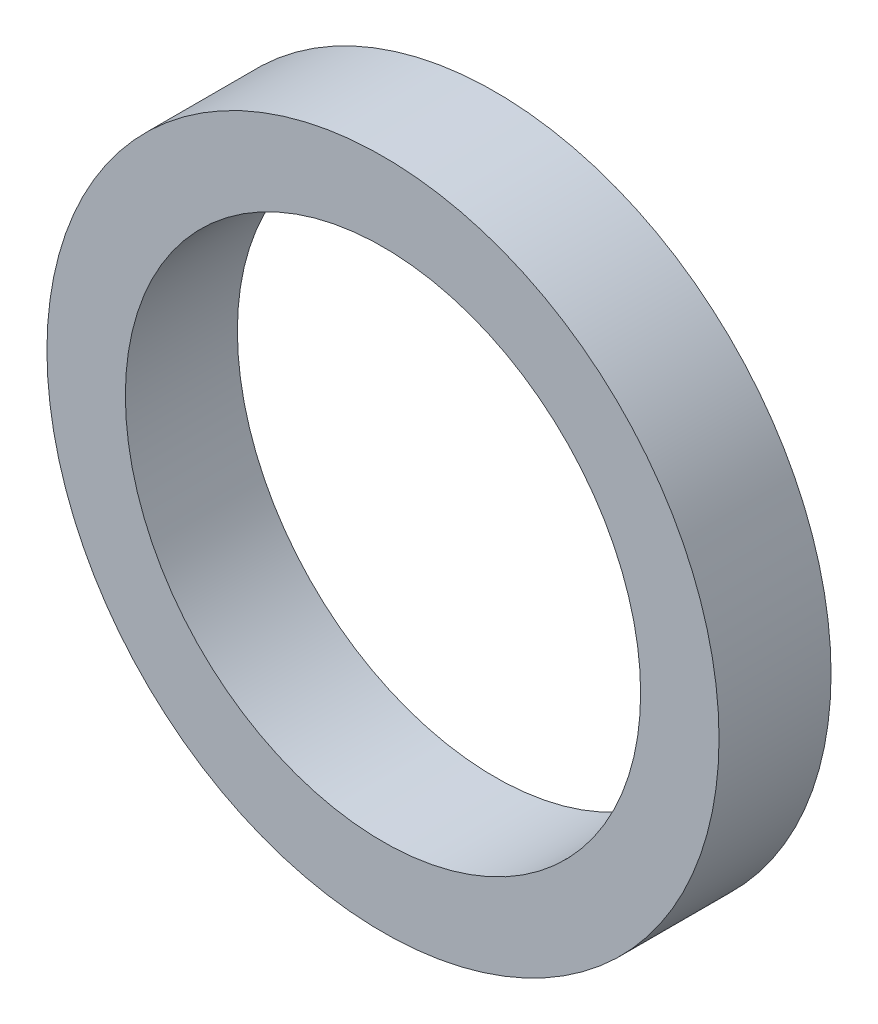
SolidWorks part; units mm, degrees
ref_plane "Plan de face" through (0, 0, 0) normal (0, 0, 1) x (1, 0, 0)
ref_plane "Plan de dessus" through (0, 0, 0) normal (0, 1, 0) x (1, 0, 0)
ref_plane "Plan de droite" through (0, 0, 0) normal (1, 0, 0) x (0, 0, -1)
sketch "Esquisse1" plane through (0, 0, 0) normal (0, 0, 1) x (1, 0, 0)
  circle A0 centre (0, 0) radius 15
  circle A1 centre (0, 0) radius 11.5
  dimension "D1" = 30
  dimension "D2" = 23
extrude "Boss.-Extru.1" add sketch "Esquisse1" along normal blind 5
